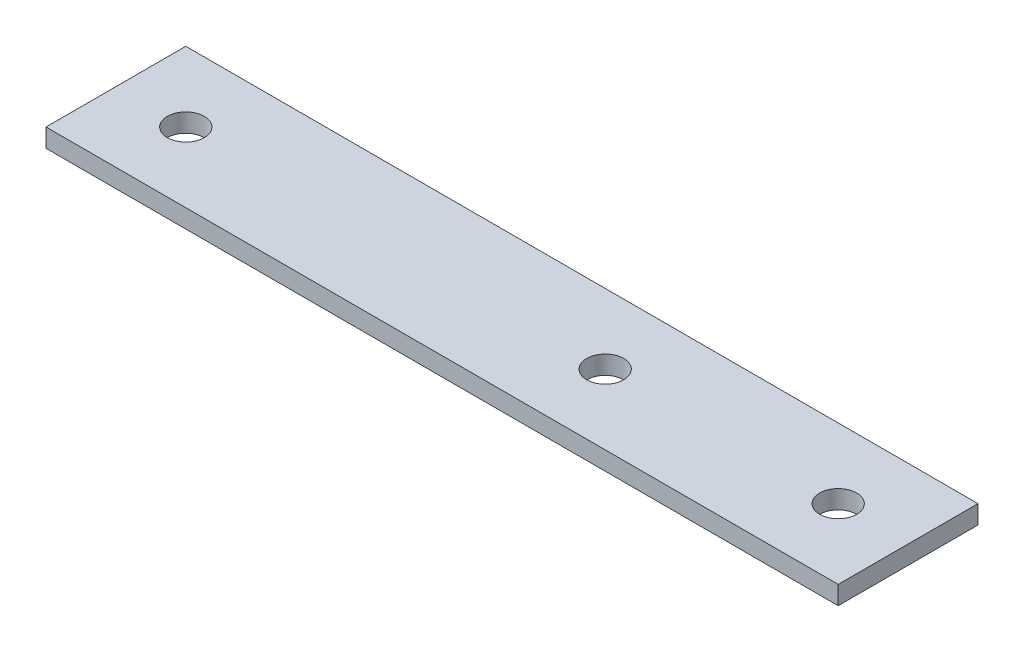
SolidWorks part; units mm, degrees
ref_plane "Front Plane" through (0, 0, 0) normal (0, 0, 1) x (1, 0, 0)
ref_plane "Top Plane" through (0, 0, 0) normal (0, 1, 0) x (1, 0, 0)
ref_plane "Right Plane" through (0, 0, 0) normal (1, 0, 0) x (0, 0, -1)
sketch "Sketch1" plane through (0, 0, 0) normal (0, 1, 0) x (1, 0, 0)
  line L0 (-28, 0) -> (28, 0) construction
  line L1 (34, -6) -> (-34, -6)
  line L2 (34, -6) -> (34, 6)
  line L3 (34, 6) -> (-34, 6)
  line L4 (-34, -6) -> (-34, 6)
  line L5 (34, -6) -> (-34, 6) construction
  line L6 (34, 6) -> (-34, -6) construction
  circle A0 centre (-28, 0) radius 1.5875
  circle A1 centre (28, 0) radius 1.5875
  circle A2 centre (-28, 0) radius 5 construction
  circle A3 centre (8, 0) radius 1.5875
  point P0 (0, 0)
  point P8 (0, 0)
  dimension "D1" = 3.175
  dimension "D4" = 10
  dimension "D2" = 56
  dimension "D3" = 12
  dimension "D5" = 6
  dimension "D6" = 20
extrude "Boss-Extrude1" add sketch "Sketch1" along normal mid plane 1.5875
